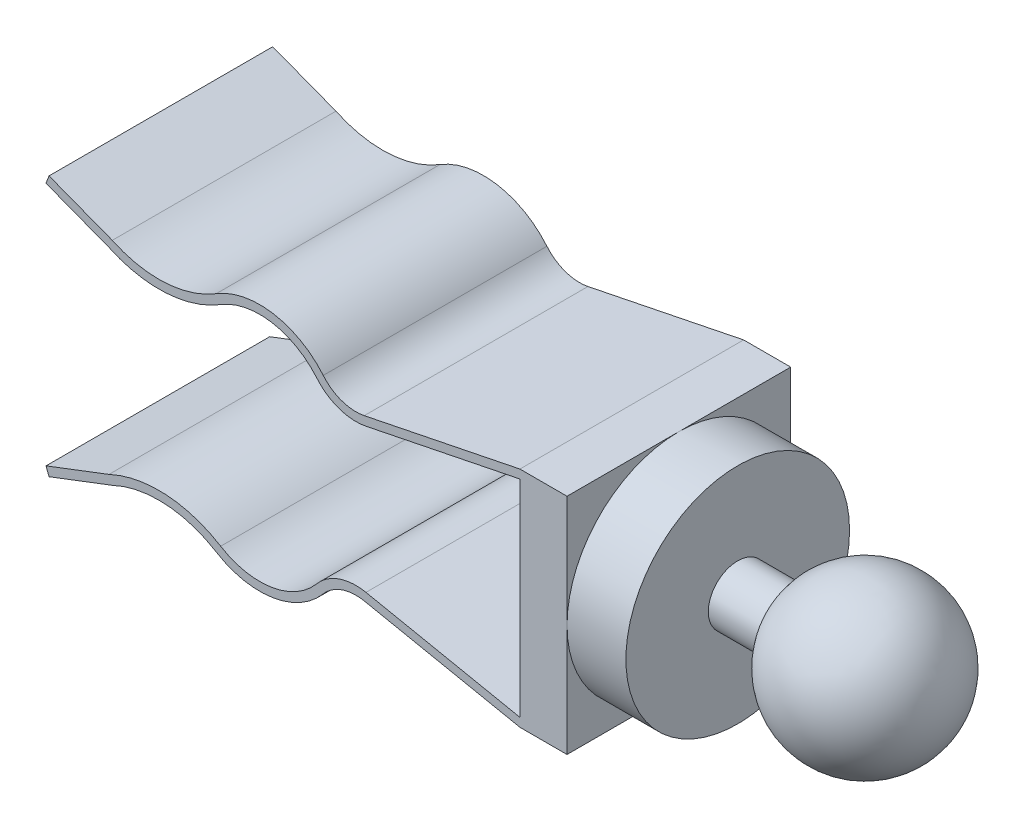
SolidWorks part; units mm, degrees
material "AISI Type 316L stainless steel"
ref_plane "Front Plane" through (0, 0, 0) normal (0, 0, 1) x (1, 0, 0)
ref_plane "Top Plane" through (0, 0, 0) normal (0, 1, 0) x (1, 0, 0)
ref_plane "Right Plane" through (0, 0, 0) normal (1, 0, 0) x (0, 0, -1)
sketch "Sketch2" plane through (0, 0, 0) normal (1, 0, 0) x (0, 0, -1)
  circle A0 centre (0, 0) radius 6.0325
  dimension "D1" = 12.065
extrude "Boss-Extrude1" add sketch "Sketch2" along normal blind 3.175
sketch "Sketch3" plane through (3.175, 0, 0) normal (1, 0, 0) x (0, 0, -1)
  circle A0 centre (0, 0) radius 1.5875
  dimension "D1" = 3.175
extrude "Boss-Extrude2" add sketch "Sketch3" along normal blind 3.175
sketch "Sketch4" plane through (0, 0, 0) normal (0, 0, 1) x (1, 0, 0)
  line L0 (3.175, 0) -> (5.715, 0)
  line L1 (3.175, -1.5875) -> (3.175, 1.5875) construction
  line L2 (5.715, 0) -> (14.351, 0)
  arc A0 (14.351, 0) -> (5.715, 0) centre (10.033, 0) ccw
  point P9 (0, 0)
  point P10 (0, 0)
  dimension "D1" = 2.54
  dimension "D2" = 8.636
revolve "Revolve1" add sketch "Sketch4" angle 360 about L2
sketch "Sketch5" plane through (0, 0, 0) normal (-1, 0, 0) x (0, 0, 1)
  line L1 (-6.0325, -6.0325) -> (6.0325, -6.0325)
  line L2 (-6.0325, -6.0325) -> (-6.0325, 6.0325)
  line L3 (-6.0325, 6.0325) -> (6.0325, 6.0325)
  line L4 (6.0325, -6.0325) -> (6.0325, 6.0325)
  line L5 (-6.0325, -6.0325) -> (6.0325, 6.0325) construction
  line L6 (-6.0325, 6.0325) -> (6.0325, -6.0325) construction
  point P0 (0, 0)
  dimension "D1" = 12.065
  dimension "D2" = 12.065
extrude "Boss-Extrude3" add sketch "Sketch5" along normal blind 2.54
sketch "Sketch7" plane through (0, 0, 0) normal (0, 0, 1) x (1, 0, 0)
  line L0 (-2.54, 6.0325) -> (-10.9356, 4.329)
  line L1 (-24.5288, 5.7227) -> (-27.94, 7.0271)
  line L2 (-2.4491, 5.5844) -> (-10.8447, 3.8809)
  line L4 (-24.5288, -5.7227) -> (-27.94, -7.0271)
  line L5 (-2.54, -6.0325) -> (-10.9356, -4.329)
  line L6 (-24.7082, 5.3018) -> (-28.1033, 6.6001)
  line L7 (-2.4491, -5.5844) -> (-10.8447, -3.8809)
  line L8 (-24.7082, -5.3018) -> (-28.1033, -6.6001)
  line L9 (-27.94, 7.0271) -> (-28.1033, 6.6001)
  line L10 (-28.1033, -6.6001) -> (-27.94, -7.0271)
  line L11 (-2.54, 6.0325) -> (-2.4491, 5.5844)
  line L12 (-2.4491, -5.5844) -> (-2.54, -6.0325)
  arc A0 (-10.9356, 4.329) -> (-13.1491, 5.102) centre (-11.3919, 6.578) cw
  arc A1 (-13.1491, 5.102) -> (-18.9221, 6.0325) centre (-16.5743, 2.2251) ccw
  arc A2 (-18.9221, 6.0325) -> (-24.5288, 5.7227) centre (-22.0108, 11.0414) cw
  arc A3 (-18.9221, -6.0325) -> (-24.5288, -5.7227) centre (-22.0108, -11.0414) ccw
  arc A4 (-13.1491, -5.102) -> (-18.9221, -6.0325) centre (-16.5743, -2.2251) cw
  arc A5 (-10.9356, -4.329) -> (-13.1491, -5.102) centre (-11.3919, -6.578) ccw
  arc A6 (-10.8447, 3.8809) -> (-13.4992, 4.808) centre (-11.3919, 6.578) cw
  arc A7 (-13.4992, 4.808) -> (-18.6821, 5.6433) centre (-16.5743, 2.2251) ccw
  arc A8 (-18.6821, 5.6433) -> (-24.7082, 5.3018) centre (-22.0108, 11.0414) cw
  arc A9 (-10.8447, -3.8809) -> (-13.4992, -4.808) centre (-11.3919, -6.578) ccw
  arc A10 (-13.4992, -4.808) -> (-18.6821, -5.6433) centre (-16.5743, -2.2251) cw
  arc A11 (-18.6821, -5.6433) -> (-24.7082, -5.3018) centre (-22.0108, -11.0414) ccw
  dimension "D1" = 25.4
  dimension "D2" = 0.4572
  dimension "D3" = 0.4572
extrude "Boss-Extrude4" add sketch "Sketch7" along normal mid plane 12.065
